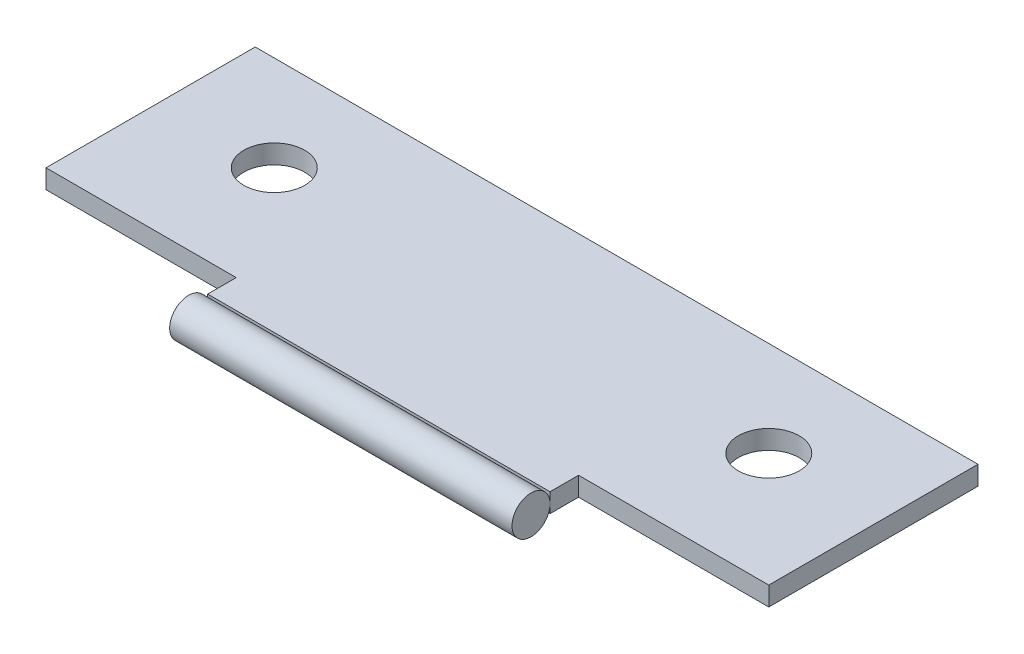
SolidWorks part; units mm, degrees
ref_plane "前视基准面" through (0, 0, 0) normal (0, 0, 1) x (1, 0, 0)
ref_plane "上视基准面" through (0, 0, 0) normal (0, 1, 0) x (1, 0, 0)
ref_plane "右视基准面" through (0, 0, 0) normal (1, 0, 0) x (0, 0, -1)
sketch "草图1" plane through (0, 0, 0) normal (0, 1, 0) x (1, 0, 0)
  line L0 (0, 0) -> (0, -10.2678) construction
  line L1 (-19, 5.5) -> (19, 5.5)
  line L2 (-19, 5.5) -> (-19, -5.5)
  line L3 (-19, -5.5) -> (-9, -5.5)
  line L4 (19, 5.5) -> (19, -5.5)
  line L5 (-19, 5.5) -> (19, -5.5) construction
  line L6 (-19, -5.5) -> (19, 5.5) construction
  line L7 (-9, -5.5) -> (-9, -7)
  line L8 (-9, -7) -> (9, -7)
  line L9 (9, -7) -> (9, -5.5)
  line L10 (9, -5.5) -> (19, -5.5)
  point P0 (0, 0)
  point P10 (0, -7)
  dimension "D1" = 38
  dimension "D2" = 11
  dimension "D3" = 18
  dimension "D4" = 1.5
extrude "凸台-拉伸1" add sketch "草图1" along normal blind 1
sketch "草图2" plane through (9, 0, 0) normal (1, 0, 0) x (0, 0, -1)
  line L0 (-7, 1) -> (-7, 0) construction
  circle A0 centre (-8, 0.4455) radius 1
  point P2 (-8.1548, 0.4455)
extrude "凸台-拉伸2" add sketch "草图2" against normal up to surface (18 mm away) separate body up to face at (-9, 0.5, 6.25)
sketch "草图3" plane through (0, 1, 0) normal (0, 1, 0) x (1, 0, 0)
  line L0 (-19, 5.5) -> (-19, -5.5) construction
  line L1 (19, 5.5) -> (-19, 5.5) construction
  line L2 (19, -5.5) -> (19, 5.5) construction
  circle A0 centre (-13, 0.5) radius 1.6
  circle A1 centre (13, 0.5) radius 1.6
  point P12 (13.2296, 3.4263)
  point P13 (13.0862, 2.0916)
  point P14 (13.252, 1.8152)
  dimension "D1" = 6
  dimension "D2" = 5
  dimension "D3" = 6
  dimension "D4" = 5
extrude "切除-拉伸1" cut sketch "草图3" against normal blind 1
